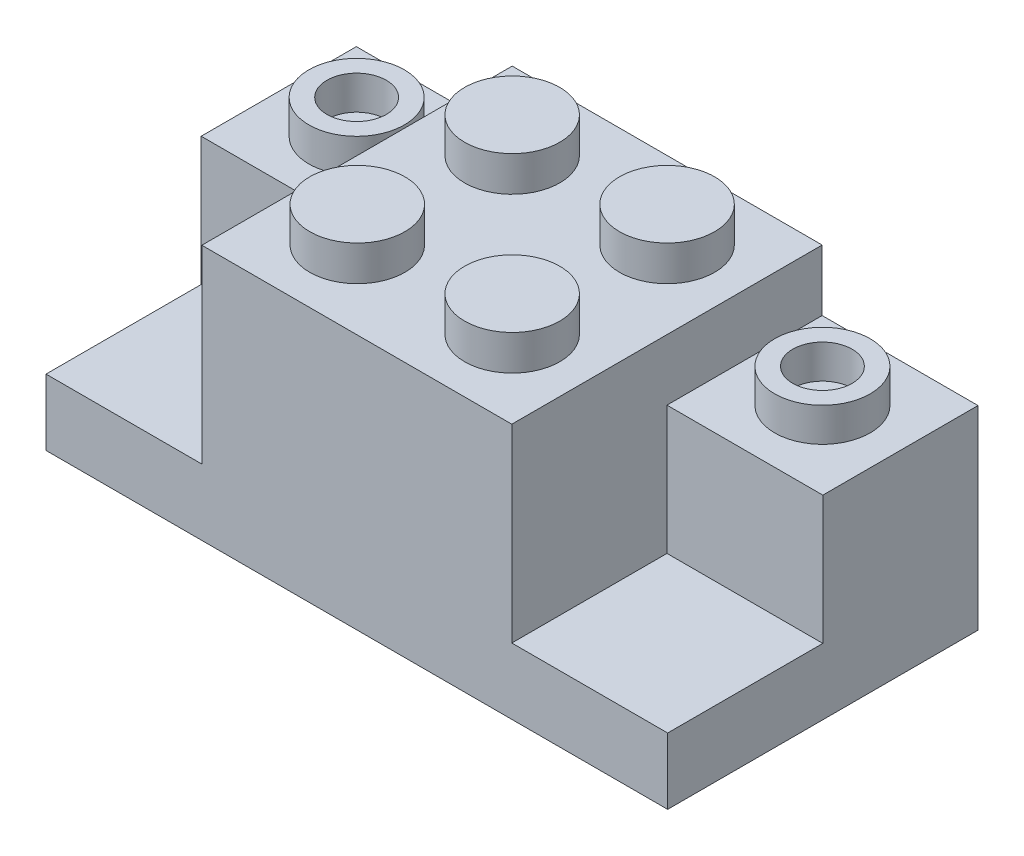
SolidWorks part; units mm, degrees
ref_plane "Front Plane" through (0, 0, 0) normal (0, 0, 1) x (1, 0, 0)
ref_plane "Top Plane" through (0, 0, 0) normal (0, 1, 0) x (1, 0, 0)
ref_plane "Right Plane" through (0, 0, 0) normal (1, 0, 0) x (0, 0, -1)
sketch "Sketch1" plane through (0, 0, 0) normal (0, 0, 1) x (1, 0, 0)
  line L0 (-7.965, 9.74) -> (7.965, 9.74)
  line L1 (7.965, 9.74) -> (7.965, 0)
  line L2 (7.965, 0) -> (15.975, 0)
  line L3 (15.975, 0) -> (15.975, -3.4)
  line L4 (15.975, -3.4) -> (-15.975, -3.4)
  line L5 (-15.975, -3.4) -> (-15.975, 0)
  line L6 (-15.975, 0) -> (-7.965, 0)
  line L7 (-7.965, 0) -> (-7.965, 9.74)
  point P4 (0, 9.74)
  point P9 (0, -3.4)
  point P11 (11.97, 0)
  dimension "D1" = 15.93
  dimension "D2" = 31.95
  dimension "D3" = 3.4
  dimension "D4" = 3.4
  dimension "D5" = 9.74
extrude "Boss-Extrude2" add sketch "Sketch1" against normal blind 15.95
sketch "Sketch2" plane through (0, 9.74, 0) normal (0, 1, 0) x (1, 0, 0)
  line L0 (-7.965, 15.95) -> (-7.965, 0) construction
  line L1 (7.965, 15.95) -> (-7.965, 15.95) construction
  line L2 (7.965, 15.95) -> (7.965, 0) construction
  circle A0 centre (-3.985, 11.97) radius 2.445
  circle A1 centre (3.975, 11.97) radius 2.445
  circle A2 centre (3.975, 4.01) radius 2.445
  circle A3 centre (-3.985, 4.01) radius 2.445
  dimension "D3" = 4.89
  dimension "D6" = 7.96
  dimension "D7" = 7.96
  dimension "D8" = 3.99
  dimension "D1" = 3.98
  dimension "D2" = 3.98
  dimension "D4" = 2
  dimension "D5" = 2
extrude "Boss-Extrude3" add sketch "Sketch2" along normal blind 1.81
sketch "Sketch3" plane through (0, 0, 0) normal (0, 1, 0) x (1, 0, 0)
  line L0 (-7.965, 15.95) -> (-7.965, 0) construction
  line L1 (-15.975, 15.95) -> (-7.965, 15.95)
  line L2 (-15.975, 15.95) -> (-15.975, 7.975)
  line L3 (-15.975, 7.975) -> (-7.965, 7.975)
  line L4 (-7.965, 15.95) -> (-7.965, 7.975)
  line L6 (-7.965, 0) -> (-15.975, 0) construction
  line L7 (0, 18.8581) -> (0, -6.6423) construction
  line L8 (7.965, 15.95) -> (7.965, 7.975)
  line L9 (15.975, 7.975) -> (7.965, 7.975)
  line L10 (15.975, 15.95) -> (15.975, 7.975)
  line L11 (15.975, 15.95) -> (7.965, 15.95)
  dimension "D1" = 7.975
extrude "Boss-Extrude4" add sketch "Sketch3" along normal offset from surface (6.6 mm away) 3.14 up to face at (-3.985, 9.74, -1.565)
sketch "Sketch4" plane through (0, 6.6, 0) normal (0, 1, 0) x (1, 0, 0)
  line L0 (15.975, 7.975) -> (15.975, 15.95) construction
  line L1 (15.975, 15.95) -> (7.965, 15.95) construction
  line L2 (0, 17.7967) -> (0, -4.0236) construction
  circle A0 centre (11.97, 11.96) radius 2.455
  circle A1 centre (11.97, 11.96) radius 1.525
  circle A2 centre (-11.97, 11.96) radius 1.525
  circle A3 centre (-11.97, 11.96) radius 2.455
  dimension "D3" = 4.91
  dimension "D4" = 3.05
  dimension "D1" = 4.005
  dimension "D2" = 3.99
extrude "Boss-Extrude5" add sketch "Sketch4" along normal blind 1.74
